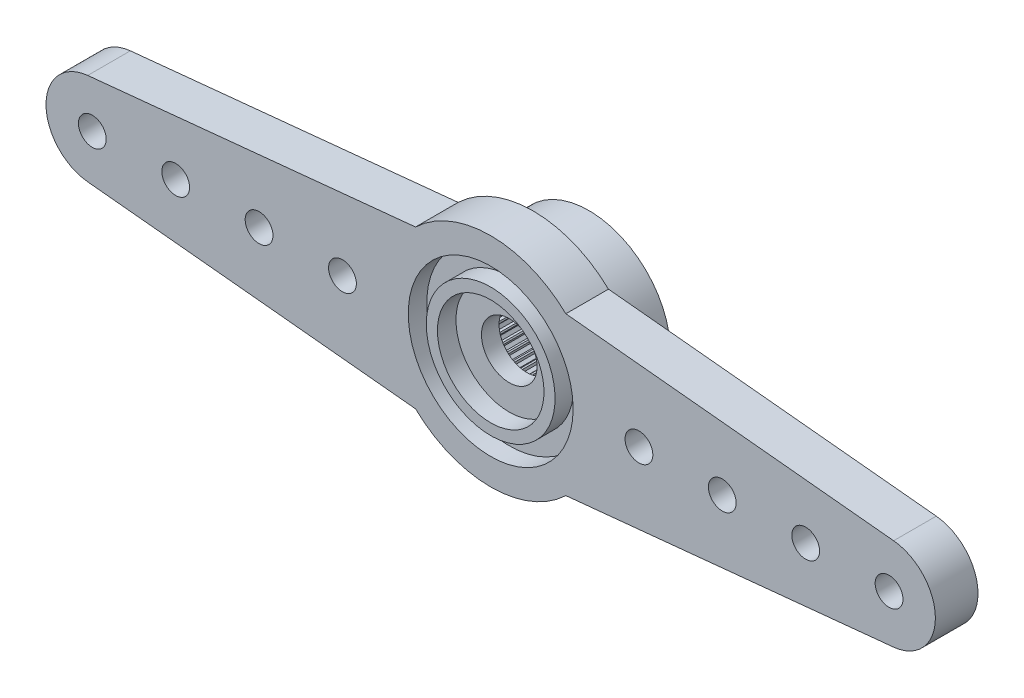
SolidWorks part; units mm, degrees
ref_plane "Plan de face" through (0, 0, 0) normal (0, 0, 1) x (1, 0, 0)
ref_plane "Plan de dessus" through (0, 0, 0) normal (0, 1, 0) x (1, 0, 0)
ref_plane "Plan de droite" through (0, 0, 0) normal (1, 0, 0) x (0, 0, -1)
sketch "Esquisse1" plane through (0, 0, 0) normal (0, 0, 1) x (1, 0, 0)
  line L0 (-21.5, 0) -> (0, 0) construction
  line L1 (-4.0562, 4.25) -> (-4.0562, -4.25) construction
  line L2 (-21.7478, 2.4877) -> (-4.0562, 4.25)
  line L3 (-21.7478, -2.4877) -> (-4.0562, -4.25)
  line L4 (0, 0) -> (0, 5.875) construction
  line L5 (21.7478, -2.4877) -> (4.0562, -4.25)
  line L6 (21.7478, 2.4877) -> (4.0562, 4.25)
  arc A0 (-4.0562, -4.25) -> (4.0562, -4.25) centre (0, 0) ccw
  arc A3 (-21.7478, 2.4877) -> (-21.7478, -2.4877) centre (-21.5, 0) ccw
  arc A4 (21.7478, 2.4877) -> (21.7478, -2.4877) centre (21.5, 0) cw
  arc A5 (4.0562, 4.25) -> (-4.0562, 4.25) centre (0, 0) ccw
  dimension "D1" = 11.75
  dimension "D2" = 2.5
  dimension "D3" = 43
  dimension "D5" = 8.5
extrude "Boss.-Extru.1" add sketch "Esquisse1" along normal blind 2.3
sketch "Esquisse2" plane through (0, 0, 2.3) normal (0, 0, 1) x (1, 0, 0)
  circle A0 centre (0, 0) radius 4.45
  dimension "D1" = 8.9
extrude "Enlèv. mat.-Extru.1" cut sketch "Esquisse2" against normal blind 1
sketch "Esquisse3" plane through (0, 0, 1.3) normal (0, 0, 1) x (1, 0, 0)
  circle A0 centre (0, 0) radius 2.875
  circle A1 centre (0, 0) radius 3.475
  dimension "D1" = 5.75
  dimension "D2" = 0.6
extrude "Boss.-Extru.2" add sketch "Esquisse3" along normal up to surface (1 mm away) up to face at (4.45, 0, 2.3)
sketch "Esquisse4" plane through (0, 0, 0) normal (0, 0, -1) x (-1, 0, 0)
  circle A0 centre (0, 0) radius 4.4
  dimension "D1" = 8.8
extrude "Boss.-Extru.3" add sketch "Esquisse4" along normal blind 3
sketch "Esquisse5" plane through (0, 0, 1.3) normal (0, 0, 1) x (1, 0, 0)
  circle A0 centre (0, 0) radius 1.5
  dimension "D1" = 3
extrude "Enlèv. mat.-Extru.2" cut sketch "Esquisse5" against normal through all
sketch "Esquisse6" plane through (0, 0, -3) normal (0, 0, -1) x (-1, 0, 0)
  line L0 (-0.1143, 2.9978) -> (-0.0406, 2.8652)
  line L1 (0.0406, 2.8652) -> (0.1143, 2.9978)
  line L2 (0, 2.8652) -> (0, 0) construction
  line L3 (-0.0406, 2.8652) -> (0.0406, 2.8652)
  line L4 (0.439, 2.8316) -> (0.5304, 2.9527)
  line L5 (0.3041, 2.9846) -> (0.3585, 2.8429)
  line L6 (0.3585, 2.8429) -> (0.439, 2.8316)
  line L7 (0.8288, 2.743) -> (0.9362, 2.8502)
  line L8 (0.7165, 2.9132) -> (0.7507, 2.7654)
  line L9 (0.7507, 2.7654) -> (0.8288, 2.743)
  line L10 (1.2025, 2.6009) -> (1.3237, 2.6922)
  line L11 (1.1149, 2.7851) -> (1.1283, 2.634)
  line L12 (1.1283, 2.634) -> (1.2025, 2.6009)
  line L13 (1.5527, 2.4083) -> (1.6855, 2.4817)
  line L14 (1.4917, 2.6029) -> (1.4839, 2.4513)
  line L15 (1.4839, 2.4513) -> (1.5527, 2.4083)
  line L16 (1.8728, 2.1687) -> (2.0145, 2.223)
  line L17 (1.8394, 2.3699) -> (1.8106, 2.2209)
  line L18 (1.8106, 2.2209) -> (1.8728, 2.1687)
  line L19 (2.1564, 1.887) -> (2.3043, 1.921)
  line L20 (2.1514, 2.0909) -> (2.1021, 1.9473)
  line L21 (2.1021, 1.9473) -> (2.1564, 1.887)
  line L22 (2.398, 1.5685) -> (2.5492, 1.5816)
  line L23 (2.4214, 1.7711) -> (2.3526, 1.6358)
  line L24 (2.3526, 1.6358) -> (2.398, 1.5685)
  line L25 (2.593, 1.2195) -> (2.7445, 1.2114)
  line L26 (2.6443, 1.4169) -> (2.5574, 1.2925)
  line L27 (2.5574, 1.2925) -> (2.593, 1.2195)
  line L28 (2.7375, 0.8468) -> (2.8864, 0.8177)
  line L29 (2.8158, 1.0351) -> (2.7124, 0.924)
  line L30 (2.7124, 0.924) -> (2.7375, 0.8468)
  line L31 (2.8287, 0.4575) -> (2.9721, 0.408)
  line L32 (2.9324, 0.6331) -> (2.8146, 0.5375)
  line L33 (2.8146, 0.5375) -> (2.8287, 0.4575)
  line L34 (2.8648, 0.0594) -> (3, -0.0096)
  line L35 (2.992, 0.2188) -> (2.862, 0.1406)
  line L36 (2.862, 0.1406) -> (2.8648, 0.0594)
  line L37 (2.8452, -0.3399) -> (2.9695, -0.427)
  line L38 (2.9933, -0.1997) -> (2.8537, -0.2591)
  line L39 (2.8537, -0.2591) -> (2.8452, -0.3399)
  line L40 (2.7702, -0.7325) -> (2.8811, -0.8361)
  line L41 (2.9364, -0.6144) -> (2.7899, -0.6537)
  line L42 (2.7899, -0.6537) -> (2.7702, -0.7325)
  line L43 (2.6413, -1.111) -> (2.7367, -1.229)
  line L44 (2.8223, -1.017) -> (2.6717, -1.0357)
  line L45 (2.6717, -1.0357) -> (2.6413, -1.111)
  line L46 (2.461, -1.4677) -> (2.5391, -1.5979)
  line L47 (2.6533, -1.3999) -> (2.5016, -1.3974)
  line L48 (2.5016, -1.3974) -> (2.461, -1.4677)
  line L49 (2.2328, -1.796) -> (2.292, -1.9357)
  line L50 (2.4327, -1.7556) -> (2.2828, -1.732)
  line L51 (2.2828, -1.732) -> (2.2328, -1.796)
  line L52 (1.9611, -2.0892) -> (2.0003, -2.2358)
  line L53 (2.1647, -2.0771) -> (2.0195, -2.0328)
  line L54 (2.0195, -2.0328) -> (1.9611, -2.0892)
  line L55 (1.6512, -2.3418) -> (1.6696, -2.4925)
  line L56 (1.8545, -2.3581) -> (1.7169, -2.2941)
  line L57 (1.7169, -2.2941) -> (1.6512, -2.3418)
  line L58 (1.3093, -2.5488) -> (1.3065, -2.7006)
  line L59 (1.5083, -2.5933) -> (1.381, -2.5107)
  line L60 (1.381, -2.5107) -> (1.3093, -2.5488)
  line L61 (0.9418, -2.7063) -> (0.9179, -2.8561)
  line L62 (1.1327, -2.7779) -> (1.0181, -2.6785)
  line L63 (1.0181, -2.6785) -> (0.9418, -2.7063)
  line L64 (0.556, -2.811) -> (0.5115, -2.9561)
  line L65 (0.7351, -2.9086) -> (0.6354, -2.7941)
  line L66 (0.6354, -2.7941) -> (0.556, -2.811)
  line L67 (0.1594, -2.861) -> (0.0951, -2.9985)
  line L68 (0.3231, -2.9825) -> (0.2404, -2.8553)
  line L69 (0.2404, -2.8553) -> (0.1594, -2.861)
  line L70 (-0.2404, -2.8553) -> (-0.3231, -2.9825)
  line L71 (-0.0951, -2.9985) -> (-0.1594, -2.861)
  line L72 (-0.1594, -2.861) -> (-0.2404, -2.8553)
  line L73 (-0.6354, -2.7941) -> (-0.7351, -2.9086)
  line L74 (-0.5115, -2.9561) -> (-0.556, -2.811)
  line L75 (-0.556, -2.811) -> (-0.6354, -2.7941)
  line L76 (-1.0181, -2.6785) -> (-1.1327, -2.7779)
  line L77 (-0.9179, -2.8561) -> (-0.9418, -2.7063)
  line L78 (-0.9418, -2.7063) -> (-1.0181, -2.6785)
  line L79 (-1.381, -2.5107) -> (-1.5083, -2.5933)
  line L80 (-1.3065, -2.7006) -> (-1.3093, -2.5488)
  line L81 (-1.3093, -2.5488) -> (-1.381, -2.5107)
  line L82 (-1.7169, -2.2941) -> (-1.8545, -2.3581)
  line L83 (-1.6696, -2.4925) -> (-1.6512, -2.3418)
  line L84 (-1.6512, -2.3418) -> (-1.7169, -2.2941)
  line L85 (-2.0195, -2.0328) -> (-2.1647, -2.0771)
  line L86 (-2.0003, -2.2358) -> (-1.9611, -2.0892)
  line L87 (-1.9611, -2.0892) -> (-2.0195, -2.0328)
  line L88 (-2.2828, -1.732) -> (-2.4327, -1.7556)
  line L89 (-2.292, -1.9357) -> (-2.2328, -1.796)
  line L90 (-2.2328, -1.796) -> (-2.2828, -1.732)
  line L91 (-2.5016, -1.3974) -> (-2.6533, -1.3999)
  line L92 (-2.5391, -1.5979) -> (-2.461, -1.4677)
  line L93 (-2.461, -1.4677) -> (-2.5016, -1.3974)
  line L94 (-2.6717, -1.0357) -> (-2.8223, -1.017)
  line L95 (-2.7367, -1.229) -> (-2.6413, -1.111)
  line L96 (-2.6413, -1.111) -> (-2.6717, -1.0357)
  line L97 (-2.7899, -0.6537) -> (-2.9364, -0.6144)
  line L98 (-2.8811, -0.8361) -> (-2.7702, -0.7325)
  line L99 (-2.7702, -0.7325) -> (-2.7899, -0.6537)
  line L100 (-2.8537, -0.2591) -> (-2.9933, -0.1997)
  line L101 (-2.9695, -0.427) -> (-2.8452, -0.3399)
  line L102 (-2.8452, -0.3399) -> (-2.8537, -0.2591)
  line L103 (-2.862, 0.1406) -> (-2.992, 0.2188)
  line L104 (-3, -0.0096) -> (-2.8648, 0.0594)
  line L105 (-2.8648, 0.0594) -> (-2.862, 0.1406)
  line L106 (-2.8146, 0.5375) -> (-2.9324, 0.6331)
  line L107 (-2.9721, 0.408) -> (-2.8287, 0.4575)
  line L108 (-2.8287, 0.4575) -> (-2.8146, 0.5375)
  line L109 (-2.7124, 0.924) -> (-2.8158, 1.0351)
  line L110 (-2.8864, 0.8177) -> (-2.7375, 0.8468)
  line L111 (-2.7375, 0.8468) -> (-2.7124, 0.924)
  line L112 (-2.5574, 1.2925) -> (-2.6443, 1.4169)
  line L113 (-2.7445, 1.2114) -> (-2.593, 1.2195)
  line L114 (-2.593, 1.2195) -> (-2.5574, 1.2925)
  line L115 (-2.3526, 1.6358) -> (-2.4214, 1.7711)
  line L116 (-2.5492, 1.5816) -> (-2.398, 1.5685)
  line L117 (-2.398, 1.5685) -> (-2.3526, 1.6358)
  line L118 (-2.1021, 1.9473) -> (-2.1514, 2.0909)
  line L119 (-2.3043, 1.921) -> (-2.1564, 1.887)
  line L120 (-2.1564, 1.887) -> (-2.1021, 1.9473)
  line L121 (-1.8106, 2.2209) -> (-1.8394, 2.3699)
  line L122 (-2.0145, 2.223) -> (-1.8728, 2.1687)
  line L123 (-1.8728, 2.1687) -> (-1.8106, 2.2209)
  line L124 (-1.4839, 2.4513) -> (-1.4917, 2.6029)
  line L125 (-1.6855, 2.4817) -> (-1.5527, 2.4083)
  line L126 (-1.5527, 2.4083) -> (-1.4839, 2.4513)
  line L127 (-1.1283, 2.634) -> (-1.1149, 2.7851)
  line L128 (-1.3237, 2.6922) -> (-1.2025, 2.6009)
  line L129 (-1.2025, 2.6009) -> (-1.1283, 2.634)
  line L130 (-0.7507, 2.7654) -> (-0.7165, 2.9132)
  line L131 (-0.9362, 2.8502) -> (-0.8288, 2.743)
  line L132 (-0.8288, 2.743) -> (-0.7507, 2.7654)
  line L133 (-0.3585, 2.8429) -> (-0.3041, 2.9846)
  line L134 (-0.5304, 2.9527) -> (-0.439, 2.8316)
  line L135 (-0.439, 2.8316) -> (-0.3585, 2.8429)
  circle A0 centre (0, 0) radius 3
  point P187 (0, 0)
  dimension "D1" = 6
  dimension "D2" = 45
extrude "Enlèv. mat.-Extru.3" cut sketch "Esquisse6" against normal blind 3.35
sketch "Esquisse7" plane through (0, 0, 2.3) normal (0, 0, 1) x (1, 0, 0)
  line L2 (0, -2.915) -> (0, 2.915) construction
  circle A0 centre (-21.5, 0) radius 0.75
  circle A7 centre (-17, 0) radius 0.75
  circle A8 centre (-12.5, 0) radius 0.75
  circle A9 centre (-8, 0) radius 0.75
  circle A10 centre (8, 0) radius 0.75
  circle A11 centre (12.5, 0) radius 0.75
  circle A12 centre (17, 0) radius 0.75
  circle A13 centre (21.5, 0) radius 0.75
  dimension "D1" = 1.5
  dimension "D2" = 4
extrude "Enlèv. mat.-Extru.4" cut sketch "Esquisse7" against normal blind 3.35
